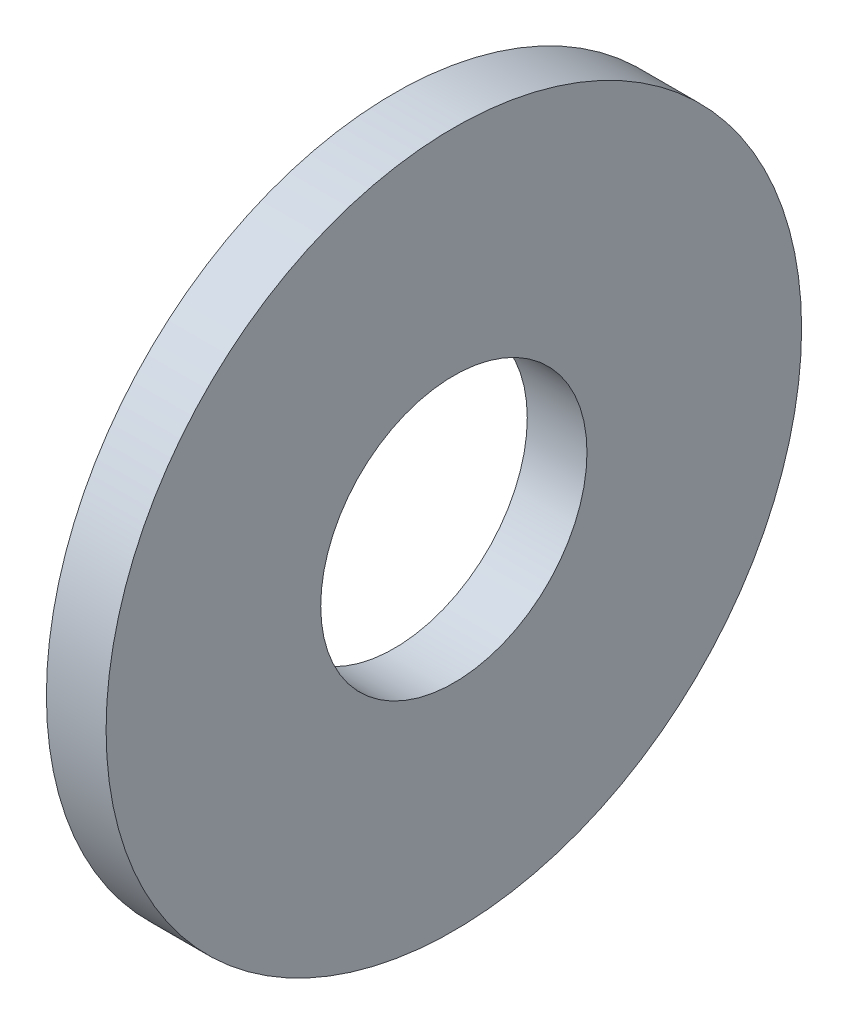
SolidWorks part; units mm, degrees
ref_plane "Front Plane" through (0, 0, 0) normal (0, 0, 1) x (1, 0, 0)
ref_plane "Top Plane" through (0, 0, 0) normal (0, 1, 0) x (1, 0, 0)
ref_plane "Right Plane" through (0, 0, 0) normal (1, 0, 0) x (0, 0, -1)
ref_plane "Plane1"
sketch "Sketch1" plane through (0, 0, 0) normal (1, 0, 0) x (0, 1, 0)
  circle A0 centre (0, 0) radius 9.3218
  circle A1 centre (0, 0) radius 3.5687
  dimension "D1" = 7.1374
  dimension "D2" = 18.6436
extrude "Body" add sketch "Sketch1" along normal blind 1.6002 contours A0 A1
